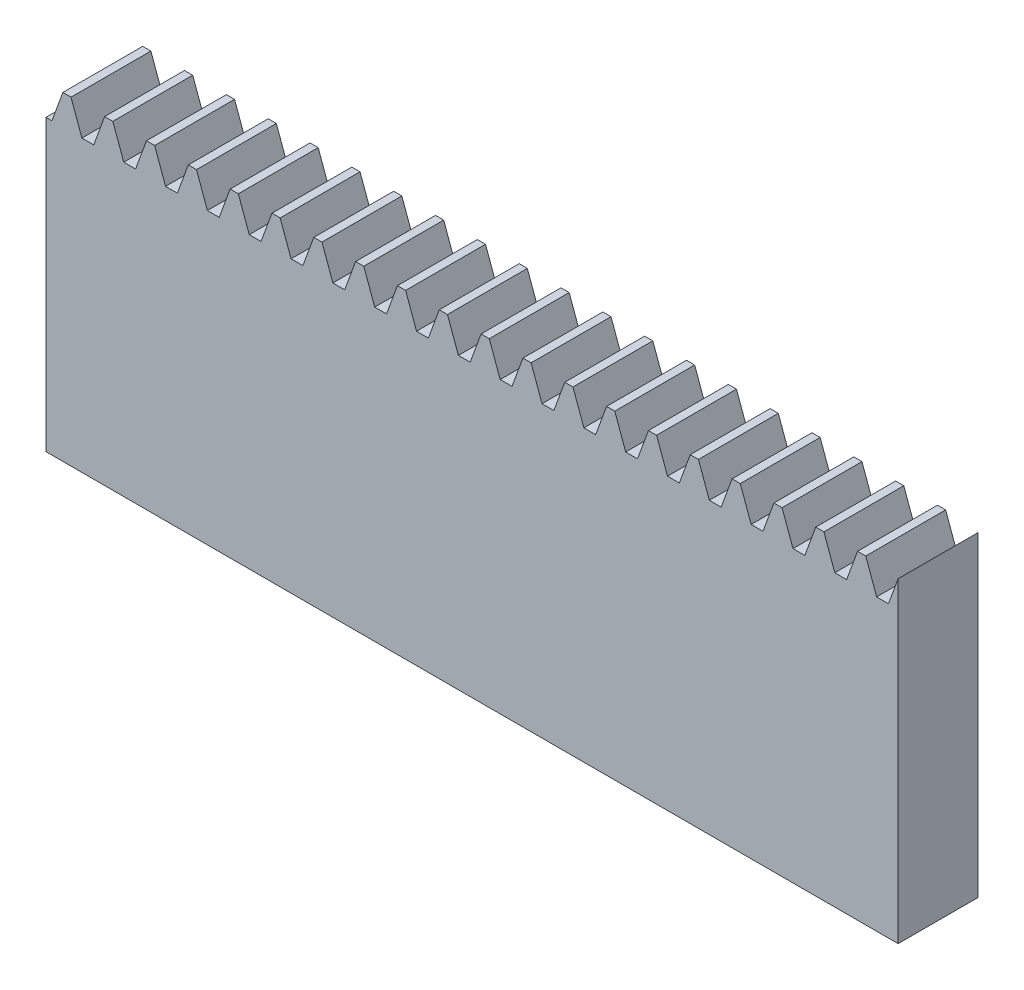
SolidWorks part; units mm, degrees
extrude "Blank" add sketch "BlankSke" against normal blind 3
sketch "BlankSke" plane through (0, 0, 0) normal (0, 0, 1) x (1, 0, 0)
  line L1 (0, 0) -> (32, 0)
  line L2 (0, 0) -> (0, 12)
  line L3 (0, 12) -> (32, 12)
  line L4 (32, 0) -> (32, 12)
  dimension "Length" = 32
  dimension "Blank_height" = 12
ref_plane "Plane1" through (0, 0, 0) normal (0, 0, 1) x (1, 0, 0)
ref_plane "Plane2" through (0, 0, 0) normal (0, 1, 0) x (1, 0, 0)
ref_plane "Plane3" through (0, 0, 0) normal (1, 0, 0) x (0, 0, -1)
sketch "HoldingSke" plane through (0, 0, 0) normal (0, 1, 0) x (1, 0, 0)
  line L0 (0, 0) -> (0.2783, 1.9805)
  line L1 (-15, 0) -> (100, 0) construction
  line L2 (0, 0) -> (-2.1039, 2.3779)
  line L3 (0, 0) -> (-11.863, 4.5341)
  line L4 (0, 0) -> (8.0072, 3.2351)
  line L5 (0, 0) -> (-23.7986, -8.8762)
  line L6 (0, 0) -> (-10.5278, -7.1032)
  line L9 (-71.009, 38.7566) -> (-40.9388, 49.7013)
  line L10 (-76.2, 2.8779) -> (-64.7, 2.8779)
  line L11 (0, 0) -> (-3, 0)
  line L12 (-76.2, 101.6) -> (-76.181, 101.6)
  line L13 (24.9733, 27.94) -> (52.9518, 28.4284)
  line L14 (24.9733, 27.94) -> (24.9743, 27.94)
  line L15 (24.9733, 27.94) -> (100.4006, 29.5858)
  circle A0 centre (0, 0) radius 19.05
  circle A1 centre (0, 0) radius 5.75
  circle A2 centre (0, 0) radius 12.7
  dimension "MPH" = 11.5
  dimension "Diameter" = 38.1
  dimension "Num_teeth" = 22
  dimension "Pitch" = 2
  dimension "Show_teeth" = 998
  dimension "Thickness" = 12.7
  dimension "Ap" = 20
  dimension "Pitch_height" = 11.5
  dimension "Width" = 3
  dimension "Backlash" = 0.019
  dimension "Addendum_fac" = 1
  dimension "Dedendum_fac" = 1.25
  dimension "Clearance_fac" = 0.25
  dimension "Dedendum_add" = 0.001
  dimension "Length" = 32
  dimension "Module" = 0.5
sketch "TooCutSkeIll" plane through (0, 0, 0) normal (0, 0, 1) x (1, 0, 0)
  line L0 (-0.6269, 11.9868) -> (-0.2524, 10.9579)
  line L1 (-0.134, 10.875) -> (0.134, 10.875)
  line L2 (0.2524, 10.9579) -> (0.6269, 11.9868)
  line L3 (32, 12) -> (0, 12) construction
  line L4 (0, 0) -> (0, 64.897) construction
  line L5 (-13.208, 11.5) -> (12.954, 11.5) construction
  line L6 (0, 0) -> (32, 0) construction
  line L7 (0.4497, 11.5) -> (0.4497, 48.7463) construction
  line L8 (-0.4497, 11.5) -> (-0.4497, 48.7463) construction
  line L9 (0.6457, 12) -> (0.6457, 12.0254)
  line L10 (-0.6457, 12) -> (-0.6457, 12.0254)
  line L11 (-0.6457, 12.0254) -> (0.6457, 12.0254)
  arc A0 (0.134, 10.875) -> (0.2524, 10.9579) centre (0.134, 11.001) ccw
  arc A1 (-0.2524, 10.9579) -> (-0.134, 10.875) centre (-0.134, 11.001) ccw
  arc A2 (0.6457, 12) -> (0.6269, 11.9868) centre (0.6457, 11.98) ccw
  arc A3 (-0.6269, 11.9868) -> (-0.6457, 12) centre (-0.6457, 11.98) ccw
  dimension "Pitch_height" = 11.5
  dimension "Addendum_plus" = 0.5254
  dimension "Pressure_angle" = 20
  dimension "Gap_width" = 0.8994
  dimension "Dedendum" = 0.625
extrude "ToothCutIll" [suppressed] cut sketch "TooCutSkeIll" against normal through all
sketch "TooCutSkeSim" plane through (0, 0, 0) normal (0, 0, 1) x (1, 0, 0)
  line L0 (0.2222, 10.875) -> (-0.2222, 10.875)
  line L1 (0.6409, 12.0254) -> (0.2222, 10.875)
  line L2 (0, 17.4625) -> (0, 53.467) construction
  line L3 (0.6409, 12.0254) -> (-0.6409, 12.0254)
  line L6 (-0.6409, 12.0254) -> (-0.2222, 10.875)
  line L9 (-0.4497, 11.5) -> (0.4497, 11.5) construction
  line L10 (0, 0) -> (32, 0) construction
  line L11 (0.4497, 11.5) -> (0.4497, 53.467) construction
  line L12 (-0.4497, 11.5) -> (-0.4497, 53.467) construction
  dimension "Pitch_height" = 11.5
  dimension "Addendum_plus" = 0.5254
  dimension "Pressure_angle" = 20
  dimension "Gap_width" = 0.8994
  dimension "Dedendum" = 0.625
extrude "ToothCutSim" cut sketch "TooCutSkeSim" against normal through all
pattern_linear "TeethCuts" count 21 spacing 1.5708 along (1, 0, 0) of "ToothCutIll", "ToothCutSim"
equation "' \"Module@HoldingSke\" = 6.35"
equation "' \"Num_teeth@HoldingSke\" = 12"
equation "' \"Ap@HoldingSke\" =  20"
equation "' \"Ap@HoldingSke\" = 20"
equation "' \"Width@HoldingSke\" = 0.25 * 25.4"
equation "' \"Show_teeth@HoldingSke\" = 500"
equation "' \"Backlash@HoldingSke\" = 0.009 * 25.4"
equation "' \"Addendum_fac@HoldingSke\" = 1.0"
equation "' \"Dedendum_fac@HoldingSke\" = 1.25"
equation "' \"Dedendum_add@HoldingSke\" = 0.00005 * 25.4"
equation "' \"Clearance_fac@HoldingSke\" = 0.25"
equation "' \"Pitch_height@HoldingSke\" = 1 * 25.4"
equation "' \"Length@HoldingSke\" = 4.71 * 25.4"
equation "\"Pitch@HoldingSke\" = 1 / \"Module@HoldingSke\""
equation "\"MPH@HoldingSke\" = \"Dedendum_fac@HoldingSke\" / \"Pitch@HoldingSke\" + 2 * \"Dedendum_add@HoldingSke\" + 0.002 * 25.4"
equation "\"MPH@HoldingSke\" = ((sgn( \"MPH@HoldingSke\" - \"Pitch_height@HoldingSke\")+1)*( \"MPH@HoldingSke\" - \"Pitch_height@HoldingSke\"))/2 + \"Pitch_height@HoldingSke\""
equation "\"Blank_height@BlankSke\" = \"Pitch_height@HoldingSke\" + \"Addendum_fac@HoldingSke\"  / \"Pitch@HoldingSke\" "
equation "\"Length@BlankSke\" =  \"Length@HoldingSke\""
equation "\"Face_width@Blank\" = \"Width@HoldingSke\""
equation "\"Pressure_angle@TooCutSkeIll\" = \"Ap@HoldingSke\""
equation "\"Addendum_plus@TooCutSkeIll\" =  \"Addendum_fac@HoldingSke\"  / \"Pitch@HoldingSke\" + 0.001 *25.4"
equation "\"Dedendum@TooCutSkeIll\" = \"Dedendum_fac@HoldingSke\"  / \"Pitch@HoldingSke\""
equation "\"Pitch_height@TooCutSkeIll\" =  \"MPH@HoldingSke\""
equation "\"Gap_width@TooCutSkeIll\" = 3.14159265 / 2 / \"Pitch@HoldingSke\" + 6 * \"Backlash@HoldingSke\""
equation "\"Pressure_angle@TooCutSkeSim\" = \"Ap@HoldingSke\""
equation "\"Addendum_plus@TooCutSkeSim\" =  \"Addendum_fac@HoldingSke\"  / \"Pitch@HoldingSke\" + 0.001 * 25.4"
equation "\"Dedendum@TooCutSkeSim\" = \"Dedendum_fac@HoldingSke\"  / \"Pitch@HoldingSke\""
equation "\"Pitch_height@TooCutSkeSim\" =  \"MPH@HoldingSke\""
equation "\"Gap_width@TooCutSkeSim\" = 3.14159265 / 2 / \"Pitch@HoldingSke\" + 6 * \"Backlash@HoldingSke\""
equation "\"Root_fillet@TooCutSkeIll\" = \"Clearance_fac@HoldingSke\" / \"Pitch@HoldingSke\" + \"Dedendum_add@HoldingSke\""
equation "\"Break_rad@TooCutSkeIll\" = 0.02 / \"Pitch@HoldingSke\" * 2"
equation "\"Linear_pitch@TeethCuts\" = 3.14159265 / \"Pitch@HoldingSke\""
equation "\"Num_teeth@HoldingSke\" = int( ( \"Length@HoldingSke\" + 0 ) / (3.14159265 / \"Pitch@HoldingSke\")) + 0.9999  + 1"
equation " \"Num_teeth@TeethCuts\" = int( \"Show_teeth@HoldingSke\" ) + 1"
equation " \"Num_teeth@TeethCuts\" = ((sgn( \"Num_teeth@TeethCuts\" - \"Num_teeth@HoldingSke\" )-1)*( \"Num_teeth@TeethCuts\" - \"Num_teeth@HoldingSke\" ))/-2+ \"Num_teeth@HoldingSke\""
equation " \"Num_teeth@TeethCuts\" = ((sgn( \"Num_teeth@TeethCuts\" - 2.0)+1)*( \"Num_teeth@TeethCuts\" - 2.0))/2 +2.0"
